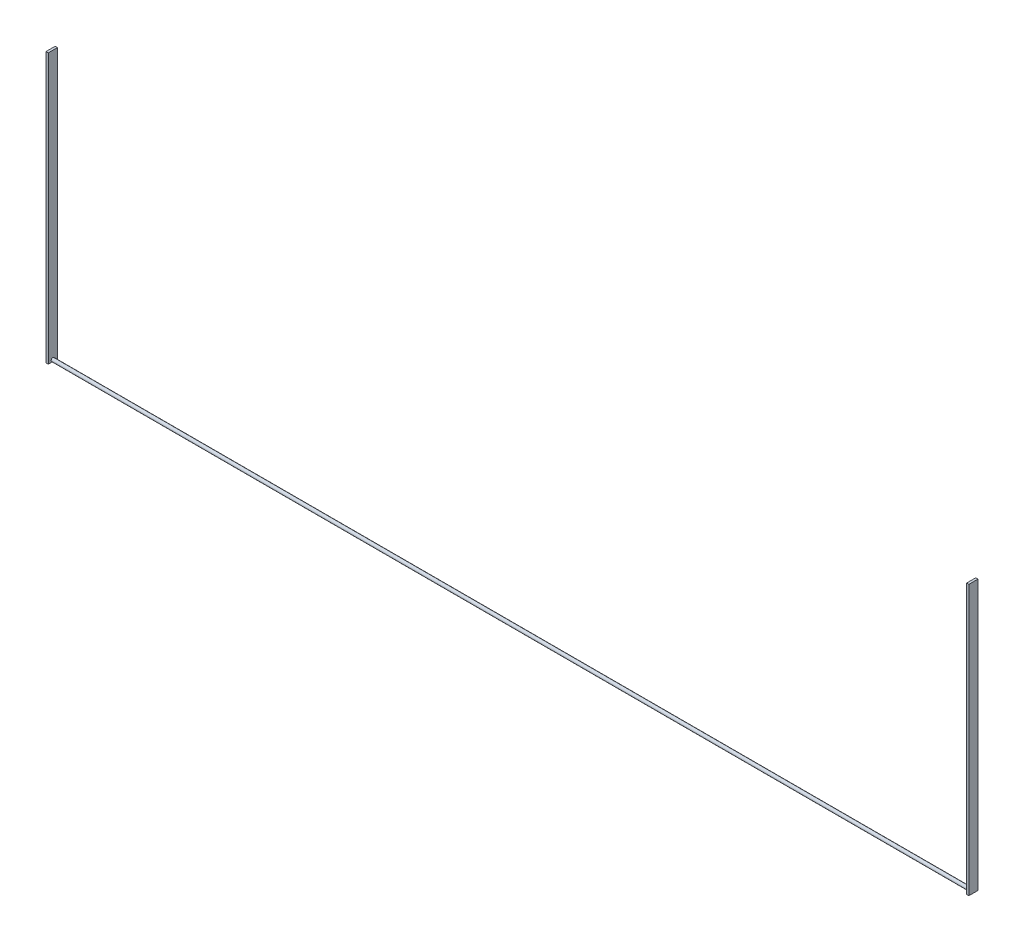
SolidWorks part; units mm, degrees
ref_plane "Alzado" through (0, 0, 0) normal (0, 0, 1) x (1, 0, 0)
ref_plane "Planta" through (0, 0, 0) normal (0, 1, 0) x (1, 0, 0)
ref_plane "Vista lateral" through (0, 0, 0) normal (1, 0, 0) x (0, 0, -1)
sketch "Croquis1" plane through (0, 0, 0) normal (0, 0, 1) x (1, 0, 0)
  line L0 (0, 0) -> (0, 750)
  line L1 (0, 750) -> (6.35, 750)
  line L2 (6.35, 750) -> (6.35, 0)
  line L3 (6.35, 0) -> (0, 0)
  line L4 (6.35, 0) -> (1283.35, 0) construction
  line L5 (1283.35, 0) -> (1283.35, 846.7279) construction
  line L6 (2560.35, 0) -> (2566.7, 0)
  line L7 (2560.35, 750) -> (2560.35, 0)
  line L8 (2566.7, 750) -> (2560.35, 750)
  line L9 (2566.7, 0) -> (2566.7, 750)
  dimension "D1" = 6.35
  dimension "D2" = 750
  dimension "D3" = 1277
extrude "Saliente-Extruir1" add sketch "Croquis1" along normal blind 25.4
sketch "Croquis2" plane through (6.35, 0, 0) normal (1, 0, 0) x (0, 0, -1)
  line L0 (-12.7, 0) -> (-12.7, 5) construction
  line L1 (-25.4, 0) -> (0, 0) construction
  circle A0 centre (-12.7, 5) radius 4.7625
  dimension "D2" = 9.525
  dimension "D1" = 5
extrude "Saliente-Extruir2" add sketch "Croquis2" along normal up to surface (2554 mm away) up to face at (2560.35, 375, 12.7)
